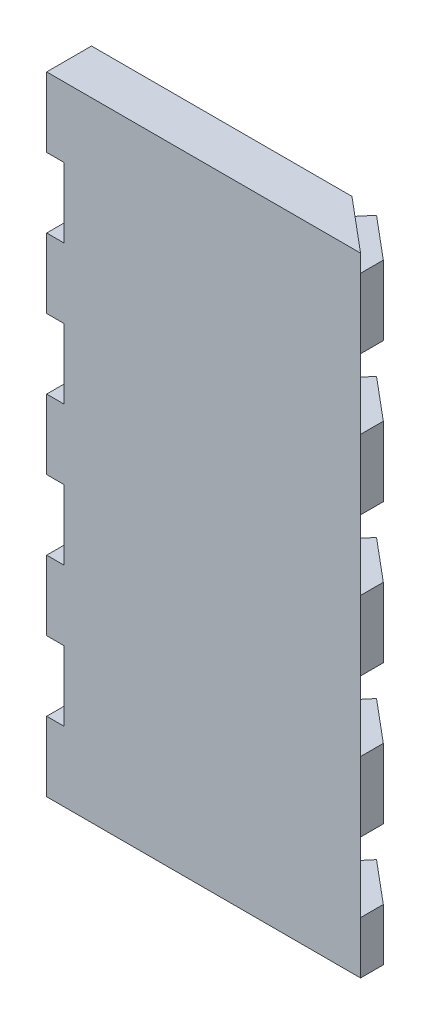
SolidWorks part; units mm, degrees
ref_plane "Front Plane" through (0, 0, 0) normal (0, 0, 1) x (1, 0, 0)
ref_plane "Top Plane" through (0, 0, 0) normal (0, 1, 0) x (1, 0, 0)
ref_plane "Right Plane" through (0, 0, 0) normal (1, 0, 0) x (0, 0, -1)
sketch "Sketch1" plane through (0, 0, 0) normal (0, 1, 0) x (1, 0, 0)
  line L0 (-53.975, 0) -> (53.975, 0)
  line L2 (53.975, 0) -> (34.5175, 16.3268)
  line L3 (34.5175, 16.3268) -> (-53.975, 16.3268)
  line L4 (-53.975, 16.3268) -> (-53.975, 0)
  point P3 (0, 0)
  point P4 (52.9093, 0)
  dimension "D1" = 107.95
  dimension "D2" = 25.4
  dimension "D3" = 40
extrude "Boss-Extrude1" add sketch "Sketch1" along normal blind 228.6
sketch "Sketch2" plane through (22.3012, 0, -26.5775) normal (0.6428, 0, -0.766) x (-0.766, 0, -0.6428)
  line L0 (-15.9472, 222.25) -> (-41.3472, 222.25)
  line L1 (-15.9472, 228.6) -> (-15.9472, 0) construction
  line L2 (-41.3472, 228.6) -> (-41.3472, 0) construction
  line L3 (-41.3472, 222.25) -> (-41.3472, 196.85)
  line L4 (-41.3472, 196.85) -> (-15.9472, 196.85)
  line L5 (-15.9472, 196.85) -> (-15.9472, 222.25)
  line L6 (-41.3472, 228.6) -> (-15.9472, 228.6) construction
  line L7 (-15.9472, 146.05) -> (-15.9472, 171.45)
  line L8 (-15.9472, 171.45) -> (-41.3472, 171.45)
  line L9 (-41.3472, 171.45) -> (-41.3472, 146.05)
  line L10 (-41.3472, 146.05) -> (-15.9472, 146.05)
  line L11 (-15.9472, 95.25) -> (-15.9472, 120.65)
  line L12 (-15.9472, 120.65) -> (-41.3472, 120.65)
  line L13 (-41.3472, 120.65) -> (-41.3472, 95.25)
  line L14 (-41.3472, 95.25) -> (-15.9472, 95.25)
  line L15 (-15.9472, 44.45) -> (-15.9472, 69.85)
  line L16 (-15.9472, 69.85) -> (-41.3472, 69.85)
  line L17 (-41.3472, 69.85) -> (-41.3472, 44.45)
  line L18 (-41.3472, 44.45) -> (-15.9472, 44.45)
  line L19 (-15.9472, 0) -> (-15.9472, 19.05)
  line L20 (-15.9472, 19.05) -> (-41.3472, 19.05)
  line L21 (-41.3472, 19.05) -> (-41.3472, 0)
  line L23 (-15.9472, 0) -> (-41.3472, 0)
  line L25 (-41.3472, -6.35) -> (-15.9472, -6.35) [skipped]
  dimension "D1" = 25.4
  dimension "D2" = 6.35
  dimension "D3" = 5
extrude "Boss-Extrude2" add sketch "Sketch2" along normal blind 6.35
sketch "Sketch3" plane through (0, 228.6, 0) normal (0, 1, 0) x (1, 0, 0)
  line L1 (53.975, 0) -> (79.375, 0)
  line L2 (53.975, 0) -> (53.975, 25.4)
  line L3 (53.975, 25.4) -> (79.375, 25.4)
  line L4 (79.375, 0) -> (79.375, 25.4)
  dimension "D1" = 25.4
  dimension "D2" = 25.4
extrude "Cut-Extrude1" cut sketch "Sketch3" against normal blind 228.6
sketch "Sketch4" plane through (-53.975, 0, 0) normal (-1, 0, 0) x (0, 0, 1)
  line L0 (0, 228.6) -> (0, 0) construction
  line L1 (-16.3268, 0) -> (0, 0)
  line L2 (-16.3268, 0) -> (-16.3268, 25.4)
  line L3 (-16.3268, 25.4) -> (0, 25.4)
  line L4 (0, 0) -> (0, 25.4)
  line L5 (-16.3268, 50.8) -> (-16.3268, 76.2)
  line L6 (-16.3268, 50.8) -> (0, 50.8)
  line L7 (0, 50.8) -> (0, 76.2)
  line L8 (-16.3268, 76.2) -> (0, 76.2)
  line L9 (-16.3268, 101.6) -> (-16.3268, 127)
  line L10 (-16.3268, 101.6) -> (0, 101.6)
  line L11 (0, 101.6) -> (0, 127)
  line L12 (-16.3268, 127) -> (0, 127)
  line L13 (-16.3268, 152.4) -> (-16.3268, 177.8)
  line L14 (-16.3268, 152.4) -> (0, 152.4)
  line L15 (0, 152.4) -> (0, 177.8)
  line L16 (-16.3268, 177.8) -> (0, 177.8)
  line L17 (-16.3268, 203.2) -> (-16.3268, 228.6)
  line L18 (-16.3268, 203.2) -> (0, 203.2)
  line L19 (0, 203.2) -> (0, 228.6)
  line L20 (-16.3268, 228.6) -> (0, 228.6)
  dimension "D1" = 25.4
  dimension "D2" = 5
extrude "Boss-Extrude3" add sketch "Sketch4" along normal blind 6.35
